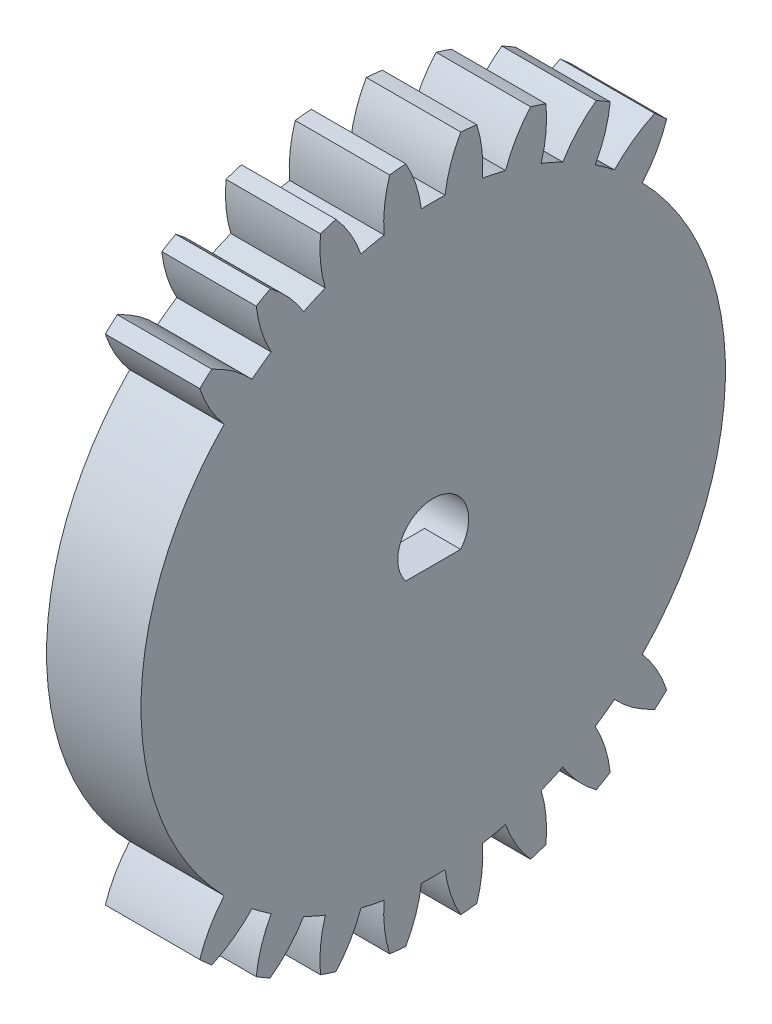
SolidWorks part; units mm, degrees
ref_plane "Plane1" through (0, 0, 0) normal (0, 0, 1) x (1, 0, 0)
ref_plane "Plane2" through (0, 0, 0) normal (0, 1, 0) x (1, 0, 0)
ref_plane "Plane3" through (0, 0, 0) normal (1, 0, 0) x (0, 0, -1)
other "Configuration Table"
sketch "HoldingSke" plane through (0, 0, 0) normal (0, 1, 0) x (1, 0, 0)
  line L0 (0, 0) -> (1.0373, -0.3982)
  line L1 (-15, 0) -> (100, 0) construction
  line L2 (0, 0) -> (-2.1039, 2.3779)
  line L3 (0, 0) -> (-11.863, 4.5341)
  line L4 (0, 0) -> (7.479, 4.318)
  line L5 (0, 0) -> (-46.8476, -17.4728)
  line L6 (0, 0) -> (-8.2896, -5.593)
  line L7 (-2.1039, 2.3779) -> (8.6586, 51.2059)
  line L8 (-76.2, 54.61) -> (-75.5, 54.61)
  line L9 (-67.7845, 28.3722) -> (-49.3413, 33.142)
  line L10 (-76.2, 71.12) -> (104.1128, 71.12)
  line L11 (0, 0) -> (-10, 0)
  line L12 (-76.2, 101.6) -> (-76.166, 101.6)
  line L13 (24.9733, 27.94) -> (52.9518, 28.4284)
  line L14 (24.9733, 27.94) -> (24.9743, 27.94)
  line L15 (24.9733, 27.94) -> (100.4006, 29.5858)
  line L16 (-63.627, -0.9) -> (-12.827, -0.9)
  circle A0 centre (0, 0) radius 2
  circle A1 centre (0, 0) radius 12.374
  circle A2 centre (0, 0) radius 37.5
  circle A3 centre (0, 0) radius 2
  dimension "MHD" = 24.748
  dimension "Hub_dia" = 75
  dimension "Bore" = 4
  dimension "MBD" = 4
  dimension "Num_teeth" = 30
  dimension "Pitch" = 1.1111
  dimension "Overall_len" = 50
  dimension "Show_teeth" = 21
  dimension "Thickness" = 10
  dimension "OAL" = 50.0001
  dimension "T_dim" = 0.7
  dimension "Ap" = 14.5
  dimension "H" = 19.05
  dimension "Pitch_radius" = 180.3128
  dimension "Width" = 10
  dimension "Backlash" = 0.034
  dimension "Addendum_fac" = 1
  dimension "Dedendum_fac" = 1.25
  dimension "Clearance_fac" = 0.25
  dimension "Dedendum_add" = 0.001
  dimension "Module" = 0.9
sketch "BasProSke" plane through (0, 0, 0) normal (0, 1, 0) x (1, 0, 0)
  line L0 (-10, 0) -> (60, 0) construction
  line L1 (0, 0) -> (0, 14.4)
  line L2 (0, 0) -> (4, 0)
  line L3 (4, 0) -> (4, 14.4)
  line L4 (4, 14.4) -> (0, 14.4)
  dimension "D1" = 4
  dimension "Diameter" = 28.8
revolve "Base-Revolve" add sketch "BasProSke" angle 360 about L0
sketch "TooCutSke" plane through (0, 0, 0) normal (1, 0, 0) x (0, 0, -1)
  line L1 (0, 0) -> (0, 107) construction
  line L2 (0, 0) -> (-0.766, 13.4782) construction
  line L3 (0, 0) -> (-2.819, 26.8212) construction
  line L4 (-0.766, 13.4782) -> (-1.4095, 13.4106) construction
  arc A0 (0.502, 12.3638) -> (-0.502, 12.3638) centre (0, 0) ccw
  arc A1 (1.1789, 14.3771) -> (-1.1789, 14.3771) centre (0, 0) ccw
  circle A2 centre (0, 0) radius 13.5 construction
  circle A3 centre (0, 0) radius 13.07 construction
  arc A4 (-0.502, 12.3638) -> (-1.1789, 14.3771) centre (-5.8589, 11.6832) ccw
  arc A5 (1.1789, 14.3771) -> (0.502, 12.3638) centre (5.8589, 11.6832) ccw
  dimension "Root_dia" = 24.748
  dimension "Overcut_dia" = 28.8508
  dimension "Pitch_dia" = 27
  dimension "Base_dia" = 26.14
  dimension "Flank_rad" = 5.4
  dimension "Half_ang" = 6
  dimension "Half_CT" = 0.647
extrude "ToothCut" cut sketch "TooCutSke" along normal through all
fillet "Breaks" [suppressed] radius 0.018
fillet "RootFillets" [suppressed] radius 0.226
pattern_circular "TeethCuts" count 30 every 12 about axis through (-10, 0, 0) along (1, 0, 0) of "ToothCut"
sketch "HubNeaOneSke" plane through (0, 0, 0) normal (-1, 0, 0) x (0, 0, 1)
  circle A0 centre (0, 0) radius 12.374
  dimension "Diameter" = 24.748
extrude "HubNearOne" [suppressed] add sketch "HubNeaOneSke" along normal blind 40.0001
sketch "HubNeaBotSke" plane through (0, 0, 0) normal (-1, 0, 0) x (0, 0, 1)
  circle A0 centre (0, 0) radius 12.374
  dimension "Diameter" = 24.748
extrude "HubNearBoth" [suppressed] add sketch "HubNeaBotSke" along normal blind 20
ref_plane "FarPln" through (10, 0, 0) normal (1, 0, 0) x (0, 0, -1)
sketch "HubFarSke" plane through (10, 0, 0) normal (1, 0, 0) x (0, 0, -1)
  circle A0 centre (0, 0) radius 12.374
  dimension "Diameter" = 24.748
extrude "HubFar" [suppressed] add sketch "HubFarSke" along normal blind 20
sketch "BorSke" plane through (0, 0, 0) normal (1, 0, 0) x (0, 0, -1)
  line L0 (-1.1608, -0.95) -> (1.1608, -0.95)
  line L1 (0, 1.5) -> (0, -0.95) construction
  arc A0 (1.1608, -0.95) -> (-1.1608, -0.95) centre (0, 0) ccw
  dimension "D1" = 2.45
  dimension "Diameter" = 3
extrude "Bore" cut sketch "BorSke" along normal mid plane 100.0001
sketch "KeySke" plane through (0, 0, 0) normal (1, 0, 0) x (0, 0, -1)
  line L0 (-0.8, 0) -> (-0.8, 2.7)
  line L1 (-0.8, 2.7) -> (0.8, 2.7)
  line L2 (0.8, 2.7) -> (0.8, 0)
  line L3 (0, 0) -> (0, 34) construction
  line L4 (-0.8, 0) -> (0.8, 0)
  dimension "Offset" = 2.7
  dimension "Width" = 1.6
extrude "Keyway" [suppressed] cut sketch "KeySke" along normal mid plane 100.0001
pattern_circular "Keyway2" [suppressed] count 2 every 90 about axis through (-10, 0, 0) along (1, 0, 0)
sketch "Sketch1" plane through (4, 0, 0) normal (1, 0, 0) x (0, 0, -1)
  line L4 (0, 12.374) -> (0, -12.374) construction
  line L9 (-9.1957, 8.2798) -> (-11.8374, 9.9904)
  line L10 (-9.0832, -8.4031) -> (-11.109, -10.7946)
  line L11 (9.0832, -8.4031) -> (11.109, -10.7946)
  line L12 (9.1957, 8.2798) -> (11.8374, 9.9904)
  arc A11 (0.502, 12.3638) -> (-0.502, 12.3638) centre (0, 0) ccw construction
  arc A12 (-0.502, -12.3638) -> (0.502, -12.3638) centre (0, 0) ccw construction
  arc A14 (-9.1957, 8.2798) -> (-9.0832, -8.4031) centre (0, 0) ccw
  arc A15 (-10.4564, 6.6167) -> (-10.9584, 5.7472) centre (0, 0) ccw construction
  arc A16 (-11.109, -10.7946) -> (-11.8374, 9.9904) centre (0, 0) cw
  arc A17 (-8.8522, 8.6461) -> (-9.524, 7.8999) centre (0, 0) ccw construction
  arc A18 (11.109, -10.7946) -> (11.8374, 9.9904) centre (0, 0) ccw
  arc A19 (9.1957, 8.2798) -> (9.0832, -8.4031) centre (0, 0) cw
extrude "Cut-Extrude2" cut sketch "Sketch1" against normal blind 10
sketch "Sketch3" plane through (0, 0, 0) normal (-1, 0, 0) x (0, 0, 1)
  circle A2 centre (0, 0) radius 1.5
  dimension "D1" = 3
extrude "Cut-Extrude3" cut sketch "Sketch3" against normal blind 2.47
equation "' \"Module@HoldingSke\" = 6.35"
equation "' \"Num_teeth@HoldingSke\" = 12"
equation "' \"Ap@HoldingSke\" =  20"
equation "' \"Ap@HoldingSke\" = 20"
equation "' \"Width@HoldingSke\" = 0.5 * 25.4"
equation "' \"Hub_dia@HoldingSke\"= 1 * 25.4"
equation "' \"Hub_dia@HoldingSke\" = 1 * 25.4"
equation "' \"Overall_len@HoldingSke\" = 1.0 * 25.4"
equation "' \"Bore@HoldingSke\" = 0.75 * 25.4"
equation "' \"T_dim@HoldingSke\" = 0.1 * 25.4"
equation "' \"Width@KeySke\" = 0.25 * 25.4"
equation "' \"Show_teeth@HoldingSke\" = 13"
equation "' \"Backlash@HoldingSke\" = 0.009 * 25.4"
equation "' \"Addendum_fac@HoldingSke\" = 1.0"
equation "' \"Dedendum_fac@HoldingSke\" = 1.25"
equation "' \"Dedendum_add@HoldingSke\" = 0.00005 * 25.4"
equation "' \"Clearance_fac@HoldingSke\" = 0.25"
equation "\"Pitch@HoldingSke\" = 1 / \"Module@HoldingSke\""
equation "\"Overcut_dia@TooCutSke\" = (\"Num_teeth@HoldingSke\" + 2 * \"Addendum_fac@HoldingSke\") / \"Pitch@HoldingSke\" + 0.002 * 25.4"
equation "\"Pitch_dia@TooCutSke\" = \"Num_teeth@HoldingSke\" / \"Pitch@HoldingSke\""
equation "\"Base_dia@TooCutSke\" = \"Num_teeth@HoldingSke\" / \"Pitch@HoldingSke\" * cos((\"Ap@HoldingSke\"  * 3.14159265 / 180))"
equation "\"Root_dia@TooCutSke\" = (\"Num_teeth@HoldingSke\" + 2) / \"Pitch@HoldingSke\" - 2 * (\"Addendum_fac@HoldingSke\" + \"Dedendum_fac@HoldingSke\") / \"Pitch@HoldingSke\" - \"Dedendum_add@HoldingSke\" * 2"
equation "\"Half_ang@TooCutSke\" = 180 / \"Num_teeth@HoldingSke\""
equation "\"Half_CT@TooCutSke\" = \"Num_teeth@HoldingSke\" / \"Pitch@HoldingSke\" * sin((3.14159265 / 2 / \"Num_teeth@HoldingSke\")) / 2 - 7 * \"Backlash@HoldingSke\" / 4"
equation "\"Flank_rad@TooCutSke\" = \"Num_teeth@HoldingSke\" / \"Pitch@HoldingSke\" / 5"
equation "\"Radius@RootFillets\" = \"Clearance_fac@HoldingSke\" / \"Pitch@HoldingSke\" + \"Dedendum_add@HoldingSke\""
equation "\"Break_rad@Breaks\" = 0.02 / \"Pitch@HoldingSke\""
equation "\"Thickness@HoldingSke\" = \"Width@HoldingSke\""
